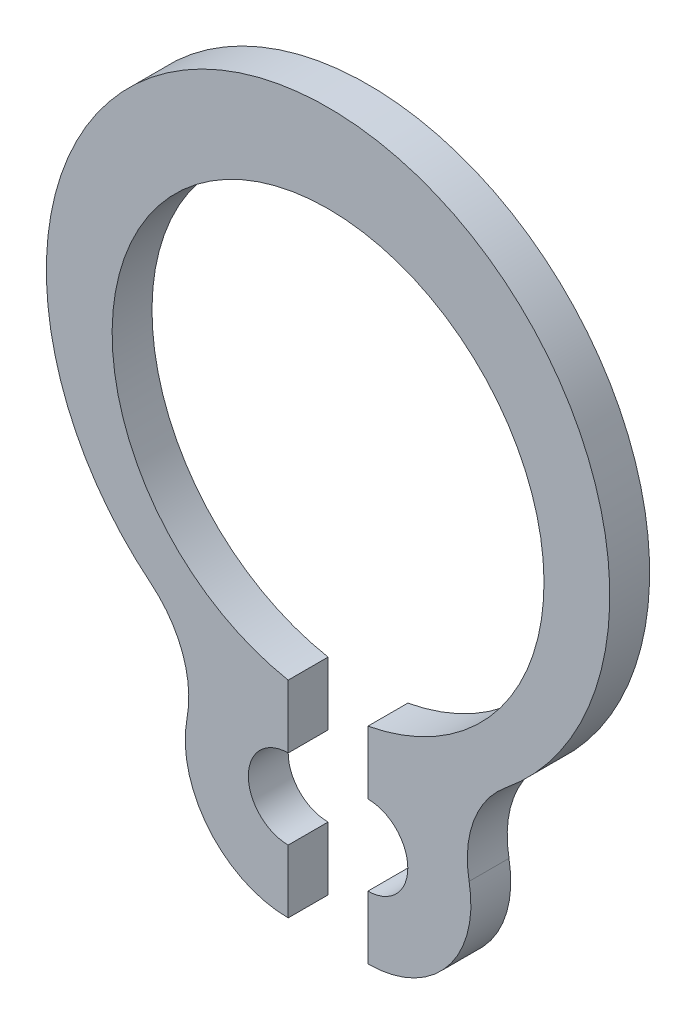
SolidWorks part; units mm, degrees
ref_plane "Front" through (0, 0, 0) normal (0, 0, 1) x (1, 0, 0)
ref_plane "Top" through (0, 0, 0) normal (0, 1, 0) x (1, 0, 0)
ref_plane "Right" through (0, 0, 0) normal (1, 0, 0) x (0, 0, -1)
sketch "Sketch1" plane through (0, 0, 0) normal (0, 0, 1) x (1, 0, 0)
  line L0 (0, -0.33) -> (0, -3.1859) construction
  line L1 (-0.6, -3.5241) -> (-0.6, -4.4741)
  line L2 (-0.6, -5.6741) -> (-0.6, -6.6241)
  line L3 (0.6, -5.6741) -> (0.6, -6.6241)
  line L4 (0.6, -3.5241) -> (0.6, -4.4741)
  arc A0 (0.6, -3.5241) -> (-0.6, -3.5241) centre (0, -0.33) ccw
  arc A1 (2.6699, -3.2938) -> (-2.6699, -3.2938) centre (0, 0) ccw
  arc A2 (-0.6, -4.4741) -> (-0.6, -5.6741) centre (-0.6, -5.0741) ccw
  arc A3 (-0.6, -6.6241) -> (-2.123, -4.786) centre (-0.6, -5.0741) cw
  arc A4 (-2.6699, -3.2938) -> (-2.123, -4.786) centre (-3.646, -4.4979) cw
  arc A5 (2.6699, -3.2938) -> (2.123, -4.786) centre (3.646, -4.4979) ccw
  arc A6 (0.6, -6.6241) -> (2.123, -4.786) centre (0.6, -5.0741) ccw
  arc A7 (0.6, -4.4741) -> (0.6, -5.6741) centre (0.6, -5.0741) cw
  dimension "d" = 6.5
  dimension "D0" = 8.48
  dimension "R3" = 1.55
  dimension "c" = 0.33
  dimension "B1" = 1.2
  dimension "d1" = 1.2
  dimension "h" = 1.55
  dimension "D2" = 1.2
extrude "Body" add sketch "Sketch1" against normal blind 0.6 separate body
equation "\"D2@Sketch1\" = \"d1@Sketch1\""
equation "\"R3@Sketch1\" = \"h@Sketch1\""
